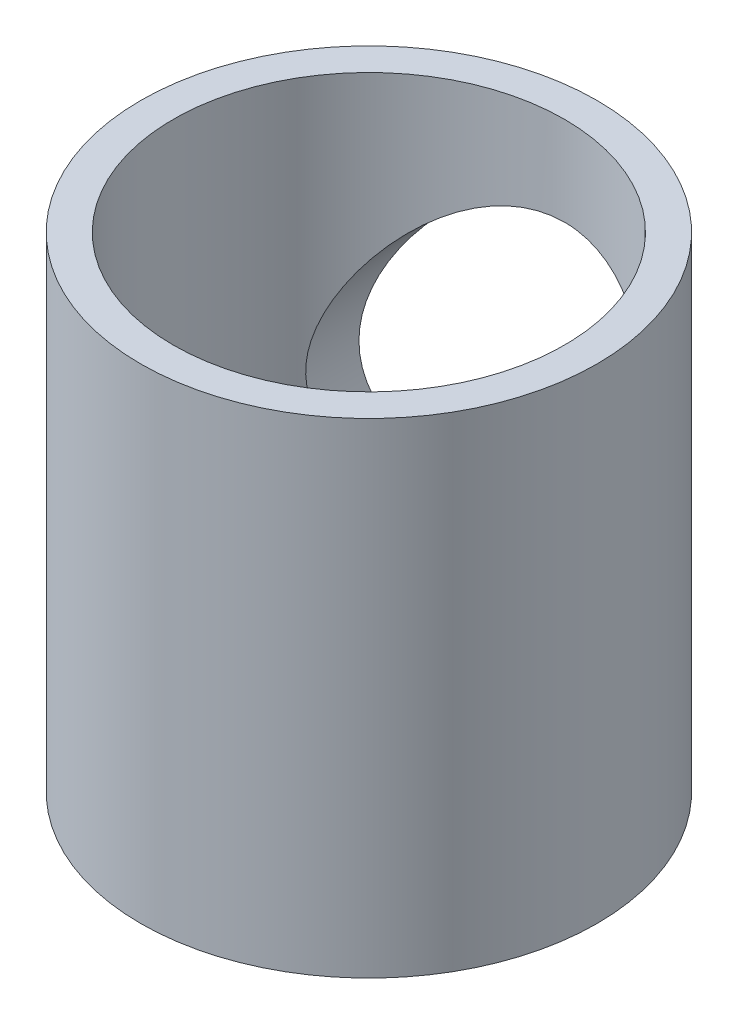
SolidWorks part; units mm, degrees
material "6061-T6 (SS)"
ref_plane "Front" through (0, 0, 0) normal (0, 0, 1) x (1, 0, 0)
ref_plane "Top" through (0, 0, 0) normal (0, 1, 0) x (1, 0, 0)
ref_plane "Right" through (0, 0, 0) normal (1, 0, 0) x (0, 0, -1)
sketch "Sketch1" plane through (0, 0, 0) normal (0, 1, 0) x (1, 0, 0)
  circle A0 centre (0, 0) radius 9
  circle A1 centre (0, 0) radius 10.5
  dimension "D1" = 18
  dimension "D2" = 21
extrude "Boss-Extrude1" add sketch "Sketch1" along normal blind 38.3
sketch "Sketch2" plane through (0, 38.3, 0) normal (0, 1, 0) x (1, 0, 0)
  line L0 (0, 10.5) -> (0, 12.5) construction
  line L1 (0, 0) -> (0, -12.5) construction
  line L2 (3, 0) -> (3, -12.5)
  line L3 (-3, 0) -> (-3, -12.5)
  line L4 (0, 0) -> (0, 12.5) construction
  line L7 (-3, 0) -> (-3, 12.5)
  line L10 (3, 0) -> (3, 12.5)
  line L11 (-1.5, -2.5981) -> (9.3253, -8.8481)
  line L12 (1.5, 2.5981) -> (12.3253, -3.6519)
  line L13 (0, 0) -> (10.8253, -6.25) construction
  line L14 (-1.5, 2.5981) -> (-12.3253, -3.6519)
  line L15 (1.5, -2.5981) -> (-9.3253, -8.8481)
  line L16 (0, 0) -> (-10.8253, -6.25) construction
  line L17 (0, 0) -> (-12.0741, 3.2352) construction
  line L18 (-0.7765, -2.8978) -> (-12.8505, 0.3375)
  line L19 (0.7765, 2.8978) -> (-11.2976, 6.133)
  line L20 (0, 36.7398) -> (0, -36.7398) construction
  line L21 (0, 0) -> (12.0741, 3.2352) construction
  line L22 (0.7765, -2.8978) -> (12.8505, 0.3375)
  line L23 (-0.7765, 2.8978) -> (11.2976, 6.133)
  circle A0 centre (0, 0) radius 9 construction
  circle A1 centre (0, 0) radius 9
  circle A2 centre (0, 0) radius 12.5
  circle A3 centre (0, 0) radius 10.5 construction
  arc A4 (3, 0) -> (-3, 0) centre (0, 0) ccw
  arc A5 (-3, -12.5) -> (3, -12.5) centre (0, -12.5) ccw
  circle A16 centre (0, -12.5) radius 1
  arc A22 (-3, 0) -> (3, 0) centre (0, 0) ccw
  arc A23 (3, 12.5) -> (-3, 12.5) centre (0, 12.5) ccw
  arc A25 (1.5, 2.5981) -> (-1.5, -2.5981) centre (0, 0) ccw
  arc A26 (9.3253, -8.8481) -> (12.3253, -3.6519) centre (10.8253, -6.25) ccw
  arc A28 (1.5, -2.5981) -> (-1.5, 2.5981) centre (0, 0) ccw
  arc A29 (-12.3253, -3.6519) -> (-9.3253, -8.8481) centre (-10.8253, -6.25) ccw
  arc A31 (-0.7765, -2.8978) -> (0.7765, 2.8978) centre (0, 0) ccw
  arc A32 (-11.2976, 6.133) -> (-12.8505, 0.3375) centre (-12.0741, 3.2352) ccw
  arc A33 (0.7765, -2.8978) -> (-0.7765, 2.8978) centre (0, 0) cw
  arc A34 (11.2976, 6.133) -> (12.8505, 0.3375) centre (12.0741, 3.2352) cw
  circle A35 centre (-12.0741, 3.2352) radius 1
  circle A36 centre (12.0741, 3.2352) radius 1
  point P8 (0, 11.5)
  point P10 (0, -6.25)
  point P19 (0, 6.25)
  point P29 (-6.037, 1.6176)
  point P31 (5.4127, -3.125)
  point P39 (-5.4127, -3.125)
  point P52 (6.037, 1.6176)
  point P55 (0, 0)
  dimension "D1" = 25
  dimension "D3" = 3
  dimension "D5" = 2
  dimension "D7" = 75
  dimension "D2" = 12.5
  dimension "D6" = 3
extrude "Boss-Extrude2" add sketch "Sketch2" along normal blind 1.5
ref_plane "Plane1" through (0, 19.15, 0) normal (0, -1, 0) x (-1, 0, 0)
fillet "Fillet1" radius 0.5 12 edges at (-3, 39.05, 12.1347) (3, 39.05, 12.1347) (9.0089, 39.05, 8.6654) (12.0089, 39.05, 3.4693) (12.4976, 39.05, -0.2429) (10.9447, 39.05, -6.0385) (3, 39.05, -12.1347) (-3, 39.05, -12.1347) (-10.9447, 39.05, -6.0385) (-12.4976, 39.05, -0.2429) (-12.0089, 39.05, 3.4693) (-9.0089, 39.05, 8.6654)
sketch "Sketch10" plane through (0, 0, 0) normal (0, 0, 1) x (1, 0, 0)
  line L0 (0, 0) -> (0, 10.55) construction
  circle A0 centre (0, 10.55) radius 7.65
  dimension "D2" = 15.3
  dimension "D1" = 10.55
extrude "Cut-Extrude1" cut sketch "Sketch10" against normal through all
sketch "Sketch15" plane through (0, 39.8, 0) normal (0, 1, 0) x (1, 0, 0)
  circle A0 centre (0, 0) radius 20.7553
extrude "Cut-Extrude3" cut sketch "Sketch15" against normal blind 17.5
